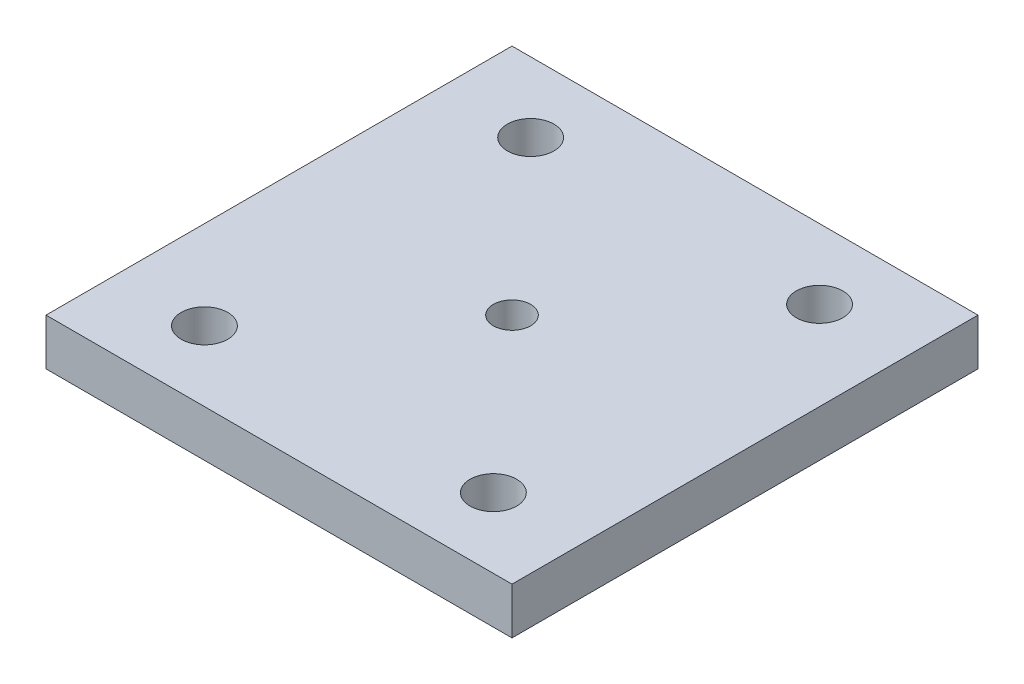
SolidWorks part; units mm, degrees
ref_plane "Front Plane" through (0, 0, 0) normal (0, 0, 1) x (1, 0, 0)
ref_plane "Top Plane" through (0, 0, 0) normal (0, 1, 0) x (1, 0, 0)
ref_plane "Right Plane" through (0, 0, 0) normal (1, 0, 0) x (0, 0, -1)
sketch "Sketch1" plane through (0, 0, 0) normal (0, 1, 0) x (1, 0, 0)
  line L1 (0, 0) -> (50, 0)
  line L2 (0, 0) -> (0, 50)
  line L3 (0, 50) -> (50, 50)
  line L4 (50, 0) -> (50, 50)
  dimension "D1" = 50
  dimension "D2" = 50
extrude "Boss-Extrude1" add sketch "Sketch1" along normal blind 5
sketch "Sketch2" plane through (0, 5, 0) normal (0, 1, 0) x (1, 0, 0)
  circle A0 centre (25, 25) radius 2
  dimension "D1" = 4
extrude "Cut-Extrude1" cut sketch "Sketch2" against normal blind 5
sketch "Sketch3" plane through (0, 0, 0) normal (0, -1, 0) x (1, 0, 0)
  circle A0 centre (40.5, -42.5) radius 2.5
  circle A1 centre (9.5, -42.5) radius 2.5
  circle A2 centre (9.5, -7.5) radius 2.5
  circle A3 centre (40.5, -7.5) radius 2.5
extrude "Cut-Extrude2" cut sketch "Sketch3" against normal blind 10
